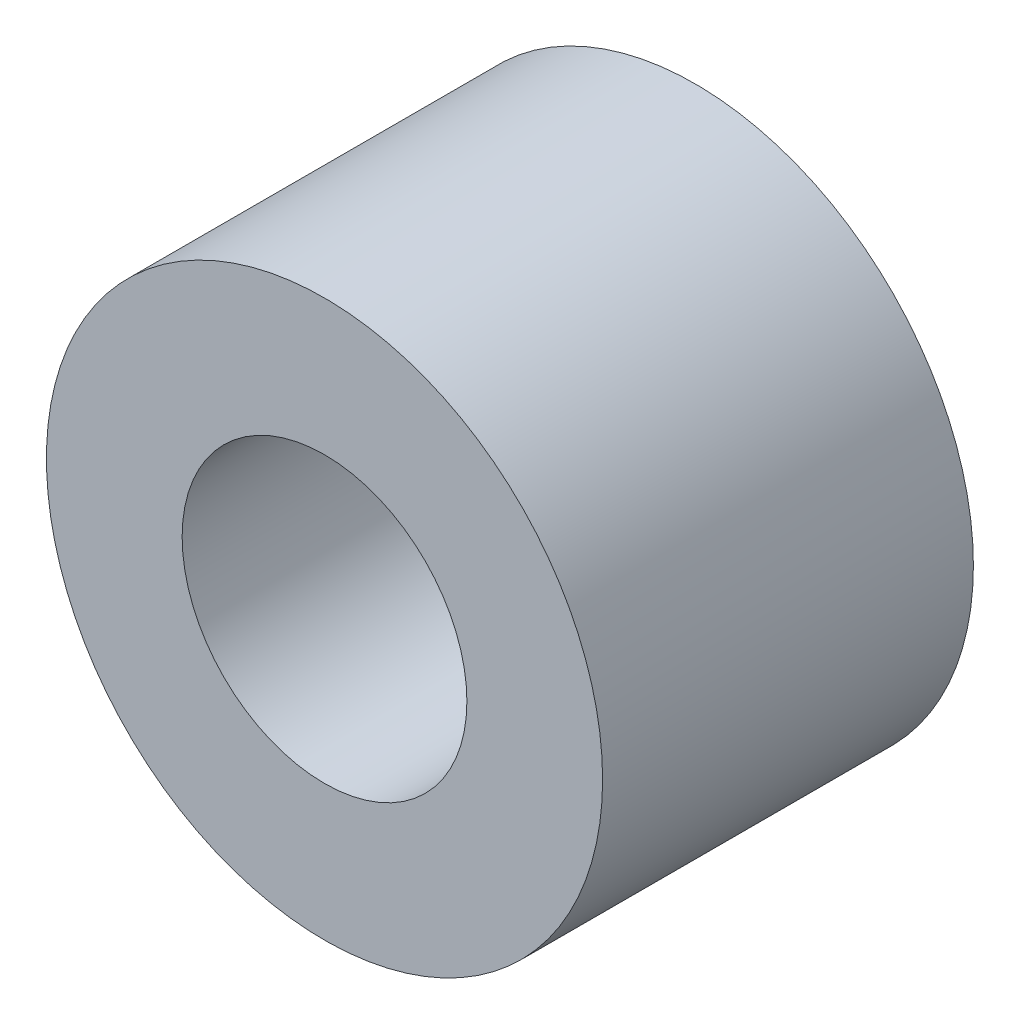
SolidWorks part; units mm, degrees
ref_plane "Front Plane" through (0, 0, 0) normal (0, 0, 1) x (1, 0, 0)
ref_plane "Top Plane" through (0, 0, 0) normal (0, 1, 0) x (1, 0, 0)
ref_plane "Right Plane" through (0, 0, 0) normal (1, 0, 0) x (0, 0, -1)
sketch "Sketch1" plane through (0, 0, 0) normal (0, 0, 1) x (1, 0, 0)
  circle A0 centre (0, 0) radius 4.7625
  circle A1 centre (0, 0) radius 2.4384
  dimension "OD" = 9.525
  dimension "ID" = 4.8768
extrude "Extrude1" add sketch "Sketch1" along normal mid plane 6.35
sketch "Sketch2" plane through (0, 0, 0) normal (1, 0, 0) x (0, 0, -1)
  line L0 (-3.175, -2.4384) -> (3.175, -2.4384) construction
  line L3 (3.175, 2.4384) -> (-3.175, 2.4384) construction
  line L5 (-3.175, -2.4384) -> (3.175, -2.4384)
  line L6 (3.175, 2.4384) -> (-3.175, 2.4384)
sketch "Sketch4" plane through (0, 0, 3.175) normal (0, 0, 1) x (1, 0, 0)
  line L0 (0, 0) -> (-1.7242, 1.7242)
  line L1 (0, -5.2388) -> (0, 5.2388) construction
  circle A0 centre (0, 0) radius 2.4384 construction
  dimension "D1" = 45
